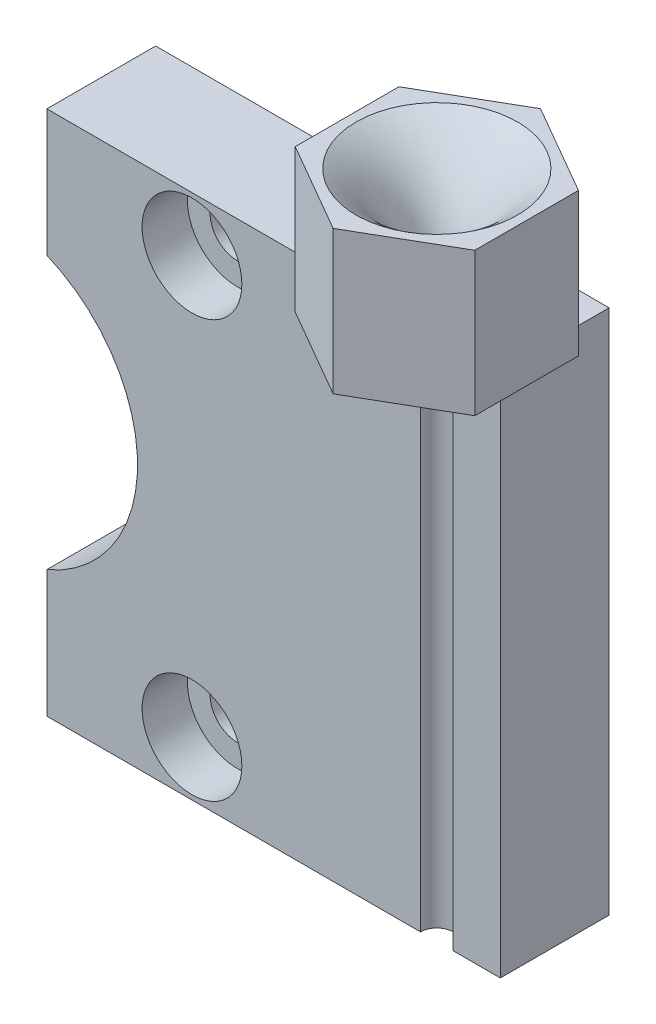
SolidWorks part; units mm, degrees
ref_plane "Front Plane" through (0, 0, 0) normal (0, 0, 1) x (1, 0, 0)
ref_plane "Top Plane" through (0, 0, 0) normal (0, 1, 0) x (1, 0, 0)
ref_plane "Right Plane" through (0, 0, 0) normal (1, 0, 0) x (0, 0, -1)
sketch "Sketch1" plane through (0, 0, 0) normal (0, 0, 1) x (1, 0, 0)
  line L0 (0, 11.5) -> (0, -11.5) construction
  line L1 (17, 14.5) -> (-8, 14.5)
  line L2 (-8, 14.5) -> (-8, 7.5)
  line L3 (-8, -14.5) -> (17, -14.5)
  line L4 (17, -14.5) -> (17, 14.5)
  line L5 (17, 0) -> (0, 0) construction
  line L6 (-1.5, 14.5) -> (-1.5, 7.5816) construction
  line L7 (-3, 4.759) -> (-3, -4.3652) construction
  line L8 (-8, -7.5) -> (-8, -14.5)
  line L9 (-3, 13) -> (5.4949, 13) construction
  circle A0 centre (0, 11.5) radius 1.5
  circle A1 centre (0, -11.5) radius 1.5
  arc A2 (-8, 7.5) -> (-8, -7.5) centre (-11.125, 0) cw
  dimension "D2" = 3
  dimension "D1" = 23
  dimension "D3" = 6.5
  dimension "D4" = 5
  dimension "D5" = 15
  dimension "D6" = 1.5
  dimension "D7" = 25
extrude "Boss-Extrude1" add sketch "Sketch1" along normal blind 6
sketch "Sketch2" plane through (0, 14.5, 0) normal (0, 1, 0) x (1, 0, 0)
  line L0 (17, -6) -> (-8, -6) construction
  circle A0 centre (13.5, -6) radius 0.9
  dimension "D1" = 1.8
  dimension "D2" = 3.5
extrude "Cut-Extrude1" cut sketch "Sketch2" against normal through all
sketch "Sketch3" plane through (0, 14.5, 0) normal (0, 1, 0) x (1, 0, 0)
  line L1 (13.5, -0.2842) -> (8.55, -3.1421)
  line L2 (8.55, -3.1421) -> (8.55, -8.8579)
  line L3 (8.55, -8.8579) -> (13.5, -11.7158)
  line L4 (13.5, -11.7158) -> (18.45, -8.8579)
  line L5 (18.45, -8.8579) -> (18.45, -3.1421)
  line L6 (18.45, -3.1421) -> (13.5, -0.2842)
  circle A0 centre (13.5, -6) radius 4.95 construction
  arc A1 (14.4, -6) -> (12.6, -6) centre (13.5, -6) ccw construction
  circle A2 centre (13.5, -6) radius 0.9
  dimension "D1" = 9.9
extrude "Boss-Extrude2" add sketch "Sketch3" along normal blind 7.9
ref_plane "Plane1" through (5.9731, 0, 10.3457) normal (0.5, 0, 0.866) x (0.866, 0, -0.5)
sketch "Sketch5" plane through (0, 22.4, 0) normal (0, 1, 0) x (1, 0, 0)
  circle A0 centre (13.5, -6) radius 4.95 construction
  circle A1 centre (13.5, -6) radius 4.95 construction
  circle A2 centre (13.5, -6) radius 4.45
  dimension "D1" = 0.5
sketch "Sketch6" plane through (5.9731, 0, 10.3457) normal (0.5, 0, 0.866) x (0.866, 0, -0.5)
  line L0 (13.6413, 22.4) -> (3.7413, 22.4) construction
  line L1 (8.6913, 22.4) -> (8.6913, 14.5) construction
  line L2 (13.6413, 14.5) -> (3.7413, 14.5) construction
  line L3 (9.5913, 14.5) -> (7.7913, 14.5) construction
  line L4 (9.5913, 22.4) -> (9.5913, 16.4)
  line L5 (13.1413, 22.4) -> (9.5913, 22.4)
  arc A0 (13.1413, 22.4) -> (9.5913, 16.4) centre (17.5635, 15.7333) ccw
  point P3 (0, 0)
  point P7 (13.6413, 22.4)
  point P15 (13.6413, 22.4)
  point P16 (0, 0)
  point P17 (12.9031, 22.4)
  point P20 (0, 0)
  dimension "D3" = 8
  dimension "D1" = 0.9
  dimension "D2" = 6
revolve "Cut-Revolve1" cut sketch "Sketch6" angle 360 about L1
hole_wizard "CBORE for M2.5 SHCS1" positions "3DSketch1" profile "Sketch7" counterbore size "M2.5" standard "ANSI Metric"
sketch3d "3DSketch1"
  point P0 (0, 11.5, 0)
  point P3 (0, -11.5, 0)
  point P6 (0, -11.5, 6)
  point P8 (0, 11.5, 6)
  point P10 (0, 0, 0)
sketch "Sketch7" plane through (0, -11.5, 6) normal (1, 0, 0) x (0, -1, 0)
  line L0 (0, 0) -> (0, 6)
  line L1 (0, 6) -> (1.45, 6)
  line L3 (1.45, 6) -> (1.45, 2.5)
  line L4 (1.45, 2.5) -> (2.75, 2.5)
  line L5 (2.75, 2.5) -> (2.75, 0)
  line L7 (2.75, 0) -> (0, 0)
  line L11 (0, -6.35) -> (0, 107.95) construction
  dimension "Thru Hole Dia." = 2.9
  dimension "Thru Hole Depth" = 6
  dimension "C'Bore Dia." = 5.5
  dimension "C'Bore Depth" = 2.5
sketch "Sketch8" plane through (0, 0, 0) normal (0, 0, -1) x (-1, 0, 0)
  circle A0 centre (0, 11.5) radius 2
  circle A1 centre (0, -11.5) radius 2
  circle A2 centre (0, 11.5) radius 1.5 construction
  circle A3 centre (0, -11.5) radius 1.5 construction
  circle A4 centre (0, -11.5) radius 1.5
  circle A5 centre (0, 11.5) radius 1.5
  dimension "D1" = 0.5
extrude "Boss-Extrude3" add sketch "Sketch8" along normal blind 1
